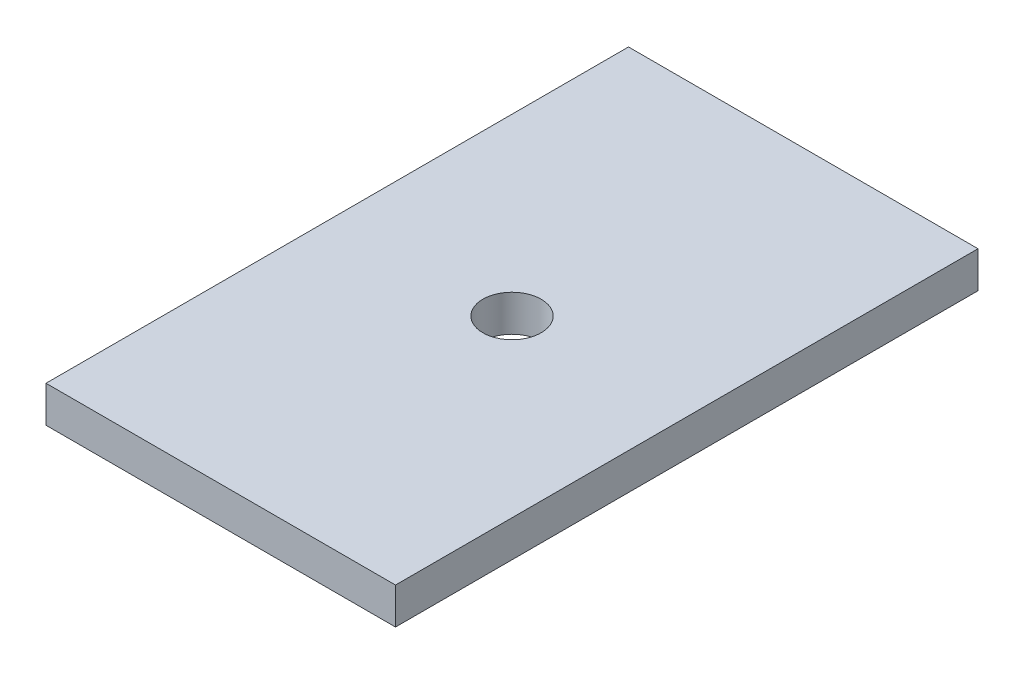
SolidWorks part; units mm, degrees
material "PW50:3:Ar:0:-1:C1:1:2:3:Re:11:"
ref_plane "front" through (0, 0, 0) normal (0, 0, 1) x (1, 0, 0)
ref_plane "top" through (0, 0, 0) normal (0, 1, 0) x (1, 0, 0)
ref_plane "side" through (0, 0, 0) normal (1, 0, 0) x (0, 0, -1)
sketch "Sketch2" plane through (0, 0, 0) normal (0, 1, 0) x (1, 0, 0)
  line L0 (152.4, 0) -> (-152.4, 0)
  line L1 (152.4, 0) -> (152.4, -508)
  line L2 (-152.4, -508) -> (152.4, -508)
  line L3 (-152.4, -508) -> (-152.4, 0)
  line L4 (0, 0) -> (0, -508) construction
  dimension "D1" = 508
  dimension "D2" = 304.8
extrude "Base-Extrude" add sketch "Sketch2" along normal blind 31.75
sketch "Sketch3" plane through (0, 31.75, 0) normal (0, 1, 0) x (-1, 0, 0)
  line L0 (-152.4, 254) -> (0, 254) construction
  line L1 (-152.4, 0) -> (-152.4, 508) construction
  line L2 (0, 0) -> (0, 254) construction
  circle A0 centre (0, 254) radius 25.4
  dimension "D1" = 50.8
extrude "Cut-Extrude1" cut sketch "Sketch3" against normal through all
sketch "pattern-sketch" [suppressed] plane through (0, 0, 0) normal (0, -1, 0) x (1, 0, 0)
  line L0 (-76.2, 469.9) -> (76.2, 469.9) construction
  line L1 (76.2, 469.9) -> (76.2, 38.1) construction
  line L2 (76.2, 38.1) -> (-76.2, 38.1) construction
  line L3 (-76.2, 38.1) -> (-76.2, 469.9) construction
  line L4 (-84.1375, 298.45) -> (84.1375, 298.45) construction
  line L5 (84.1375, 298.45) -> (84.1375, 209.55) construction
  line L6 (84.1375, 209.55) -> (-84.1375, 209.55) construction
  line L7 (-84.1375, 209.55) -> (-84.1375, 298.45) construction
  circle A16 centre (0, 254) radius 25.4 construction
  point P5 (76.2, 469.9)
  point P7 (76.2, 38.1)
  point P8 (-76.2, 38.1)
  dimension "D1" = 88.9
  dimension "D2" = 431.8
  dimension "D3" = 168.275
  dimension "D4" = 152.4
  dimension "D5" = 44.45
  dimension "D6" = 215.9
  dimension "D7" = 76.2
  dimension "D8" = 84.1375
hole_wizard "1-1/4-7 Tapped Hole1" [suppressed] positions "Sketch6" profile "Sketch5" tap size "1-1/4-7" standard "Ansi Inch"
sketch "Sketch6" plane through (0, 31.75, 0) normal (0, 1, 0) x (-1, 0, 0)
  point P0 (76.2, 469.9)
sketch "Sketch5" plane through (-76.2, 31.75, 469.9) normal (1, 0, 0) x (0, 0, 1)
  line L0 (0, 0) -> (0, 31.75)
  line L1 (0, 31.75) -> (14.0894, 31.75)
  line L2 (14.0894, 31.75) -> (14.0894, 0)
  line L5 (14.0894, 0) -> (0, 0)
  line L11 (0, -6.35) -> (0, 107.95) construction
  dimension "Thru Hole Dia." = 28.1788
  dimension "Thru Hole Depth" = 31.75
cosmetic thread "Cosmetic Thread1" parameters "D1"=31.75, "D2"=31.75
pattern_sketch "Sketch-Pattern2" [suppressed]
